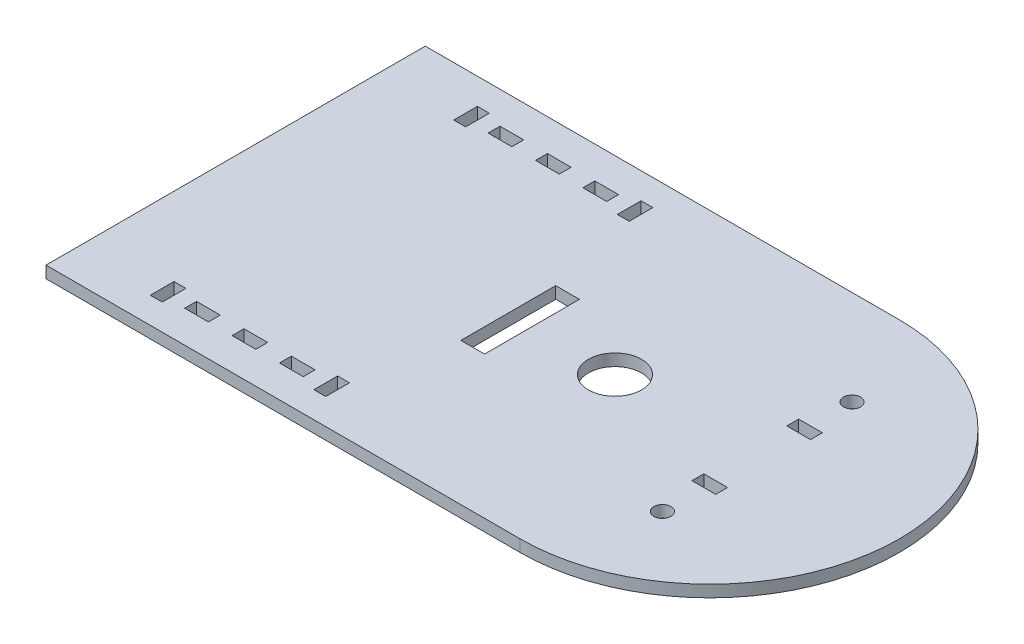
SolidWorks part; units mm, degrees
ref_plane "Front Plane" through (0, 0, 0) normal (0, 0, 1) x (1, 0, 0)
ref_plane "Top Plane" through (0, 0, 0) normal (0, 1, 0) x (1, 0, 0)
ref_plane "Right Plane" through (0, 0, 0) normal (1, 0, 0) x (0, 0, -1)
sketch "Sketch1" plane through (0, 0, 0) normal (0, 1, 0) x (1, 0, 0)
  line L5 (0, -50.8) -> (0, 50.8)
  line L6 (0, 50.8) -> (127, 50.8)
  line L9 (0, -50.8) -> (127, -50.8)
  arc A1 (127, 50.8) -> (127, -50.8) centre (127, 0) cw
  point P3 (0, 0)
  dimension "D2" = 127
  dimension "D1" = 101.6
extrude "Boss-Extrude1" add sketch "Sketch1" along normal blind 3.175
sketch "Sketch3" plane through (0, 3.175, 0) normal (0, 1, 0) x (1, 0, 0)
  line L0 (44.45, 50.8) -> (44.45, -50.8) construction
  line L1 (127, 50.8) -> (0, 50.8) construction
  line L2 (0, -50.8) -> (127, -50.8) construction
  line L3 (0, 50.8) -> (0, -50.8) construction
  line L4 (66.3575, 40.64) -> (22.5425, 40.64) construction
  line L5 (22.5425, -40.64) -> (66.3575, -40.64) construction
  line L7 (20.955, 37.465) -> (24.13, 37.465)
  line L8 (20.955, 37.465) -> (20.955, 43.815)
  line L9 (20.955, 43.815) -> (24.13, 43.815)
  line L10 (24.13, 37.465) -> (24.13, 43.815)
  line L11 (20.955, 37.465) -> (24.13, 43.815) construction
  line L12 (20.955, 43.815) -> (24.13, 37.465) construction
  line L13 (64.77, 37.465) -> (67.945, 37.465)
  line L14 (64.77, 37.465) -> (64.77, 43.815)
  line L15 (64.77, 43.815) -> (67.945, 43.815)
  line L16 (67.945, 37.465) -> (67.945, 43.815)
  line L17 (64.77, 37.465) -> (67.945, 43.815) construction
  line L18 (64.77, 43.815) -> (67.945, 37.465) construction
  line L19 (64.77, -43.815) -> (67.945, -43.815)
  line L20 (64.77, -43.815) -> (64.77, -37.465)
  line L21 (64.77, -37.465) -> (67.945, -37.465)
  line L22 (67.945, -43.815) -> (67.945, -37.465)
  line L23 (64.77, -43.815) -> (67.945, -37.465) construction
  line L24 (64.77, -37.465) -> (67.945, -43.815) construction
  line L25 (20.955, -43.815) -> (24.13, -43.815)
  line L26 (20.955, -43.815) -> (20.955, -37.465)
  line L27 (20.955, -37.465) -> (24.13, -37.465)
  line L28 (24.13, -43.815) -> (24.13, -37.465)
  line L29 (20.955, -43.815) -> (24.13, -37.465) construction
  line L30 (20.955, -37.465) -> (24.13, -43.815) construction
  point P11 (44.45, 40.64)
  point P14 (44.45, -40.64)
  dimension "D1" = 44.45
  dimension "D2" = 43.815
  dimension "D3" = 3.175
  dimension "D4" = 6.35
  dimension "D5" = 10.16
  dimension "D6" = 10.16
extrude "Cut-Extrude2" cut sketch "Sketch3" against normal up to next
sketch "Sketch4" plane through (0, 3.175, 0) normal (0, 1, 0) x (1, 0, 0)
  line L0 (177.8, 0) -> (139.7, 0) construction
  line L6 (139.7, 31.75) -> (139.7, 25.4) construction
  line L7 (152.4, 31.75) -> (127, 31.75) construction
  line L12 (152.4, 31.75) -> (152.4, -31.75) construction
  line L13 (152.4, -31.75) -> (127, -31.75) construction
  line L17 (127, 31.75) -> (127, -31.75) construction
  line L18 (152.4, 31.75) -> (127, -31.75) construction
  line L23 (152.4, -31.75) -> (127, 31.75) construction
  arc A0 (127, -50.8) -> (127, 50.8) centre (127, 0) ccw construction
  circle A1 centre (139.7, 25.4) radius 2.286
  circle A3 centre (139.7, -25.4) radius 2.286
  dimension "D4" = 4.572
  dimension "D1" = 38.1
  dimension "D2" = 63.5
  dimension "D3" = 25.4
  dimension "D5" = 6.35
extrude "Cut-Extrude3" cut sketch "Sketch4" against normal up to next
sketch "Sketch5" plane through (0, 3.175, 0) normal (0, 1, 0) x (1, 0, 0)
  line L0 (0, 0) -> (139.7, 0) construction
  line L3 (0, 50.8) -> (0, -50.8) construction
  line L6 (139.7, 12.7) -> (139.7, -12.7) construction
  line L7 (136.525, -14.2875) -> (142.875, -14.2875)
  line L8 (136.525, -14.2875) -> (136.525, -11.1125)
  line L9 (136.525, -11.1125) -> (142.875, -11.1125)
  line L10 (142.875, -14.2875) -> (142.875, -11.1125)
  line L11 (136.525, -14.2875) -> (142.875, -11.1125) construction
  line L12 (136.525, -11.1125) -> (142.875, -14.2875) construction
  line L13 (136.525, 11.1125) -> (142.875, 11.1125)
  line L14 (136.525, 11.1125) -> (136.525, 14.2875)
  line L15 (136.525, 14.2875) -> (142.875, 14.2875)
  line L16 (142.875, 11.1125) -> (142.875, 14.2875)
  line L17 (136.525, 11.1125) -> (142.875, 14.2875) construction
  line L18 (136.525, 14.2875) -> (142.875, 11.1125) construction
  point P12 (139.7, -12.7)
  point P17 (139.7, 12.7)
  dimension "D1" = 6.35
  dimension "D2" = 3.175
  dimension "D3" = 25.4
  dimension "D4" = 139.7
extrude "Cut-Extrude4" cut sketch "Sketch5" against normal blind 3.175
sketch "Sketch6" plane through (0, 3.175, 0) normal (0, 1, 0) x (1, 0, 0)
  line L0 (64.77, 40.64) -> (24.13, 40.64) construction
  line L1 (64.77, 43.815) -> (64.77, 37.465) construction
  line L2 (24.13, 37.465) -> (24.13, 43.815) construction
  line L3 (44.45, 40.64) -> (44.45, -40.64) construction
  line L4 (64.77, -40.64) -> (24.13, -40.64) construction
  line L5 (64.77, -37.465) -> (64.77, -43.815) construction
  line L6 (24.13, -43.815) -> (24.13, -37.465) construction
  line L8 (41.275, 42.2275) -> (47.625, 42.2275)
  line L9 (41.275, 42.2275) -> (41.275, 39.0525)
  line L10 (41.275, 39.0525) -> (47.625, 39.0525)
  line L11 (47.625, 42.2275) -> (47.625, 39.0525)
  line L12 (41.275, 42.2275) -> (47.625, 39.0525) construction
  line L13 (41.275, 39.0525) -> (47.625, 42.2275) construction
  line L14 (41.275, -39.0525) -> (47.625, -39.0525)
  line L15 (41.275, -39.0525) -> (41.275, -42.2275)
  line L16 (41.275, -42.2275) -> (47.625, -42.2275)
  line L17 (47.625, -39.0525) -> (47.625, -42.2275)
  line L18 (41.275, -39.0525) -> (47.625, -42.2275) construction
  line L19 (41.275, -42.2275) -> (47.625, -39.0525) construction
  line L20 (53.975, 42.2275) -> (60.325, 42.2275)
  line L21 (53.975, 42.2275) -> (53.975, 39.0525)
  line L22 (53.975, 39.0525) -> (60.325, 39.0525)
  line L23 (60.325, 42.2275) -> (60.325, 39.0525)
  line L24 (53.975, 42.2275) -> (60.325, 39.0525) construction
  line L25 (53.975, 39.0525) -> (60.325, 42.2275) construction
  line L26 (34.925, 42.2275) -> (28.575, 42.2275)
  line L27 (34.925, 42.2275) -> (34.925, 39.0525)
  line L28 (34.925, 39.0525) -> (28.575, 39.0525)
  line L29 (28.575, 42.2275) -> (28.575, 39.0525)
  line L30 (34.925, 42.2275) -> (28.575, 39.0525) construction
  line L31 (34.925, 39.0525) -> (28.575, 42.2275) construction
  line L32 (34.925, -39.0525) -> (28.575, -39.0525)
  line L33 (34.925, -39.0525) -> (34.925, -42.2275)
  line L34 (34.925, -42.2275) -> (28.575, -42.2275)
  line L35 (28.575, -39.0525) -> (28.575, -42.2275)
  line L36 (34.925, -39.0525) -> (28.575, -42.2275) construction
  line L37 (34.925, -42.2275) -> (28.575, -39.0525) construction
  line L38 (60.325, -39.0525) -> (53.975, -39.0525)
  line L39 (60.325, -39.0525) -> (60.325, -42.2275)
  line L40 (60.325, -42.2275) -> (53.975, -42.2275)
  line L41 (53.975, -39.0525) -> (53.975, -42.2275)
  line L42 (60.325, -39.0525) -> (53.975, -42.2275) construction
  line L43 (60.325, -42.2275) -> (53.975, -39.0525) construction
  point P15 (44.45, -40.64)
  point P23 (57.15, 40.64)
  point P28 (31.75, 40.64)
  point P33 (31.75, -40.64)
  point P38 (57.15, -40.64)
  dimension "D1" = 3.175
  dimension "D2" = 6.35
  dimension "D3" = 6.35
  dimension "D4" = 6.35
  dimension "D5" = 6.35
  dimension "D6" = 6.35
  dimension "D7" = 81.28
extrude "Cut-Extrude5" cut sketch "Sketch6" against normal blind 3.175
sketch "Sketch7" plane through (0, 3.175, 0) normal (0, 1, 0) x (1, 0, 0)
  line L0 (76.2, 50.8) -> (76.2, -50.8) construction
  line L1 (127, 50.8) -> (0, 50.8) construction
  line L2 (0, -50.8) -> (127, -50.8) construction
  line L3 (0, 50.8) -> (0, -50.8) construction
  line L4 (76.2, 0) -> (101.6, 0) construction
  line L5 (73.025, 12.7) -> (79.375, 12.7)
  line L6 (73.025, 12.7) -> (73.025, -12.7)
  line L7 (73.025, -12.7) -> (79.375, -12.7)
  line L8 (79.375, 12.7) -> (79.375, -12.7)
  line L9 (73.025, 12.7) -> (79.375, -12.7) construction
  line L10 (73.025, -12.7) -> (79.375, 12.7) construction
  circle A0 centre (101.6, 0) radius 7.112
  point P8 (76.2, 0)
  dimension "D5" = 14.224
  dimension "D1" = 76.2
  dimension "D2" = 6.35
  dimension "D3" = 25.4
  dimension "D4" = 25.4
extrude "Cut-Extrude6" cut sketch "Sketch7" against normal blind 3.175
